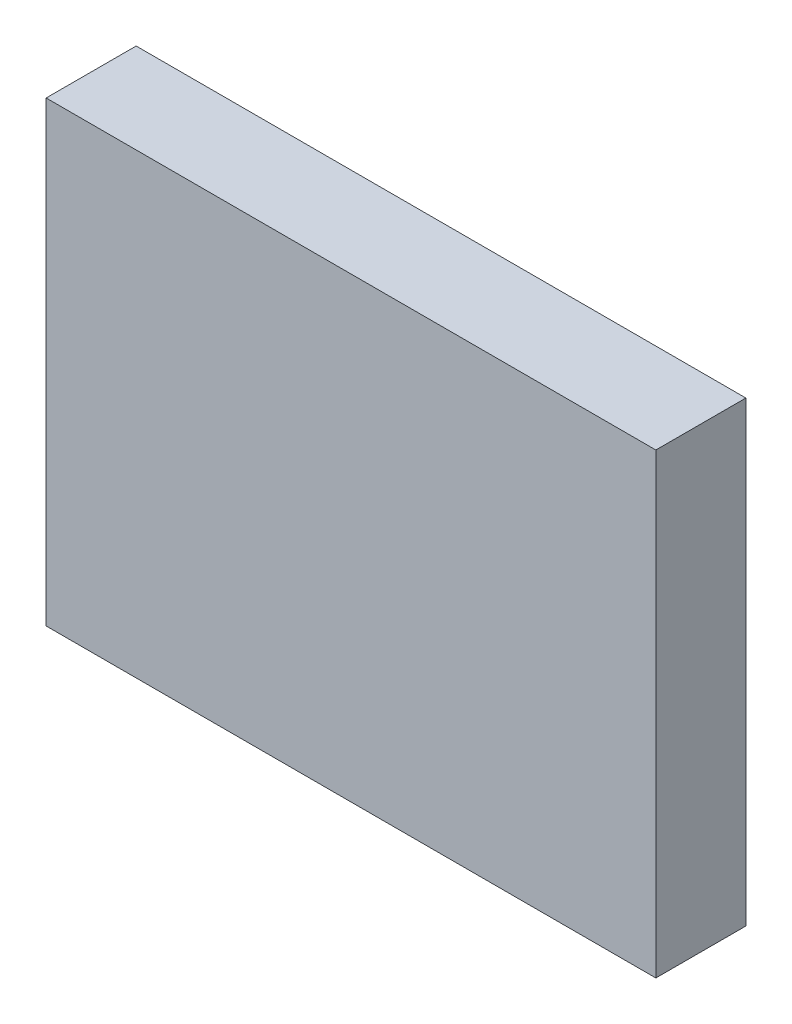
SolidWorks part; units mm, degrees
material "轻木"
ref_plane "Front" through (0, 0, 0) normal (0, 0, 1) x (1, 0, 0)
ref_plane "Top" through (0, 0, 0) normal (0, 1, 0) x (1, 0, 0)
ref_plane "Right" through (0, 0, 0) normal (1, 0, 0) x (0, 0, -1)
sketch "草图1" plane through (0, 0, 0) normal (0, 0, 1) x (1, 0, 0)
  line L1 (0, 0) -> (101.6, 0)
  line L2 (0, 0) -> (0, -76.2)
  line L3 (0, -76.2) -> (101.6, -76.2)
  line L4 (101.6, 0) -> (101.6, -76.2)
  dimension "D1" = 101.6
  dimension "D2" = 76.2
extrude "凸台-拉伸1" add sketch "草图1" along normal blind 15
